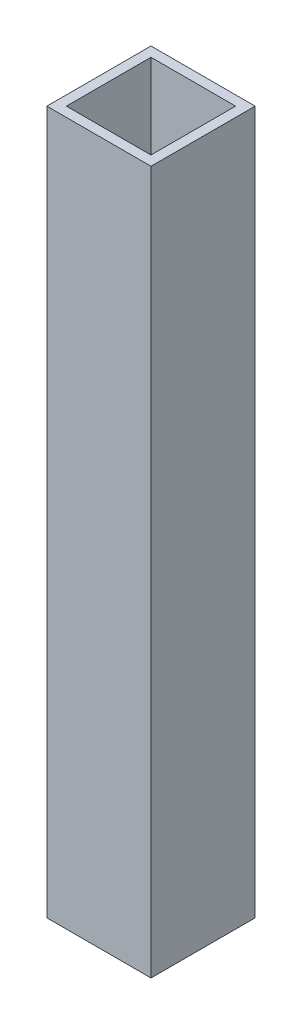
SolidWorks part; units mm, degrees
ref_plane "Front Plane" through (0, 0, 0) normal (0, 0, 1) x (1, 0, 0)
ref_plane "Top Plane" through (0, 0, 0) normal (0, 1, 0) x (1, 0, 0)
ref_plane "Right Plane" through (0, 0, 0) normal (1, 0, 0) x (0, 0, -1)
sketch "Sketch1" plane through (0, 0, 0) normal (0, 0, 1) x (1, 0, 0)
  line L1 (-25.4, 171.45) -> (25.4, 171.45)
  line L2 (-25.4, 171.45) -> (-25.4, -171.45)
  line L3 (-25.4, -171.45) -> (25.4, -171.45)
  line L4 (25.4, 171.45) -> (25.4, -171.45)
  line L5 (-25.4, 171.45) -> (25.4, -171.45) construction
  line L6 (-25.4, -171.45) -> (25.4, 171.45) construction
  point P0 (0, 0)
  dimension "D1" = 50.8
  dimension "D2" = 342.9
extrude "Boss-Extrude1" add sketch "Sketch1" along normal blind 50.8
sketch "Sketch3" plane through (0, 171.45, 0) normal (0, 1, 0) x (1, 0, 0)
  line L8 (-20.6375, -4.7625) -> (-20.6375, -46.0375)
  line L9 (-20.6375, -46.0375) -> (20.6375, -46.0375)
  line L10 (20.6375, -46.0375) -> (20.6375, -4.7625)
  line L11 (20.6375, -4.7625) -> (-20.6375, -4.7625)
  line L12 (-20.6375, -4.7625) -> (-20.6375, -46.0375)
  line L13 (-20.6375, -46.0375) -> (20.6375, -46.0375)
  line L14 (20.6375, -46.0375) -> (20.6375, -4.7625)
  line L15 (20.6375, -4.7625) -> (-20.6375, -4.7625)
  dimension "D1" = 4.7625
extrude "Cut-Extrude1" cut sketch "Sketch3" against normal up to next
